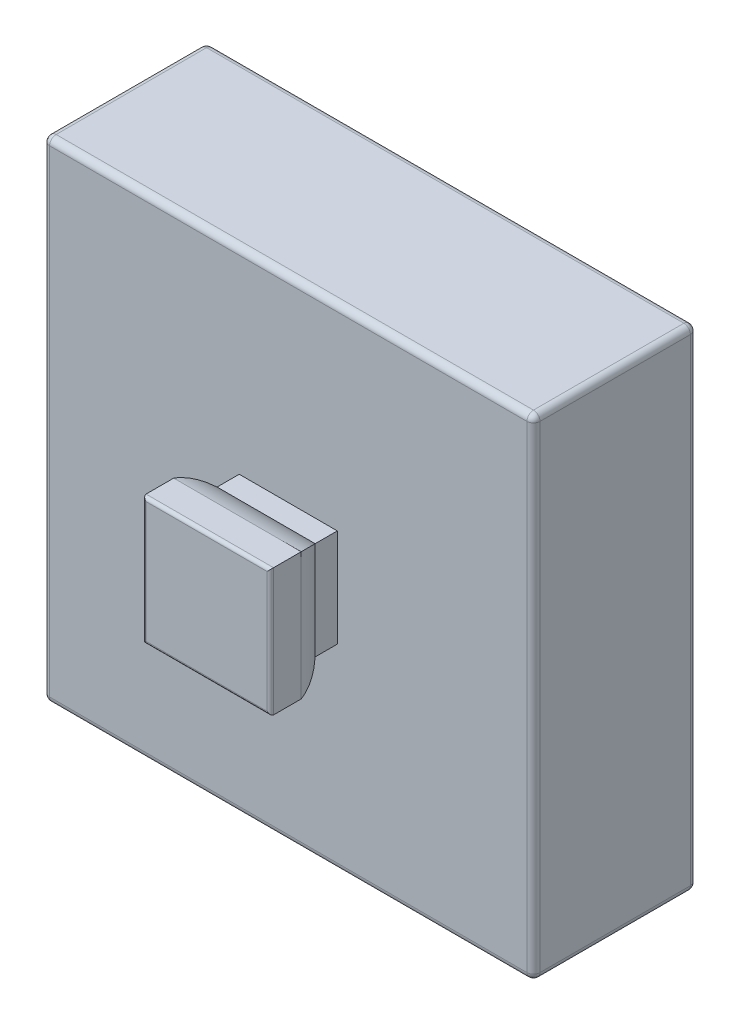
SolidWorks part; units mm, degrees
ref_plane "前视基准面" through (0, 0, 0) normal (0, 0, 1) x (1, 0, 0)
ref_plane "上视基准面" through (0, 0, 0) normal (0, 1, 0) x (1, 0, 0)
ref_plane "右视基准面" through (0, 0, 0) normal (1, 0, 0) x (0, 0, -1)
sketch "草图1" plane through (0, 0, 0) normal (0, 0, 1) x (1, 0, 0)
  line L1 (-7.5, -7.5) -> (7.5, -7.5)
  line L2 (-7.5, -7.5) -> (-7.5, 7.5)
  line L3 (-7.5, 7.5) -> (7.5, 7.5)
  line L4 (7.5, -7.5) -> (7.5, 7.5)
extrude "凸台-拉伸1" add sketch "草图1" against normal blind 5
sketch "草图2" plane through (0, 0, 0) normal (0, 0, 1) x (1, 0, 0)
  line L1 (-1.5, -1.5) -> (1.5, -1.5)
  line L2 (-1.5, -1.5) -> (-1.5, 1.5)
  line L3 (-1.5, 1.5) -> (1.5, 1.5)
  line L4 (1.5, -1.5) -> (1.5, 1.5)
extrude "凸台-拉伸2" add sketch "草图2" along normal blind 1
sketch "草图3" plane through (0, 0, 0) normal (0, 1, 0) x (1, 0, 0)
  line L0 (-1.95, -2.5) -> (1.95, -2.5)
  line L1 (-1.95, -2.5) -> (-1.95, -1.5556)
  line L2 (-1.5, -1) -> (-1.5, 0) construction
  line L3 (-1.5, -0.6771) -> (1.5, -0.6771)
  line L4 (1.95, -2.5) -> (1.95, -1.5556)
  arc A0 (1.95, -1.5556) -> (1.5, -0.6771) centre (0, -2) ccw
  arc A1 (-1.5, -0.6771) -> (-1.95, -1.5556) centre (0, -2) ccw
extrude "凸台-拉伸3" add sketch "草图3" along normal blind 2 and the other way blind 2
sketch "草图4" plane through (0, 0, 0) normal (1, 0, 0) x (0, 0, -1)
  line L0 (-2.5, 1.95) -> (-1.5556, 1.95)
  line L1 (-2.5, 1.95) -> (-2.5, 2)
  line L2 (-2.5, -2) -> (-2.5, 2) construction
  line L3 (-2.5, 2) -> (-0.6771, 2)
  line L4 (-0.6771, 2) -> (-0.6771, 1.5)
  line L5 (-2.5, -2) -> (-0.6771, -2)
  line L6 (-0.6771, -2) -> (-0.6771, -1.5)
  line L7 (-2.5, -1.95) -> (-1.5556, -1.95)
  line L8 (-2.5, -1.95) -> (-2.5, -2)
  arc A0 (-0.6771, 1.5) -> (-1.5556, 1.95) centre (-2, 0) ccw
  arc A2 (-1.5556, -1.95) -> (-0.6771, -1.5) centre (-2, 0) ccw
extrude "切除-拉伸1" cut sketch "草图4" against normal up to next and the other way up to next
fillet "圆角1" radius 0.1 4 edges at (0, -1.95, 2.5) (-1.95, 0, 2.5) (0, 1.95, 2.5) (1.95, 0, 2.5)
ref_plane "基准面1" through (0, 0, -2.5) normal (0, 0, 1) x (1, 0, 0)
mirror "镜向1" about plane through (0, 0, -2.5) normal (0, 0, 1) of "凸台-拉伸2", "凸台-拉伸3", "切除-拉伸1", "圆角1"
fillet "圆角2" radius 0.2 12 edges at (0, -7.5, -5) (0, -7.5, 0) (-7.5, -7.5, -2.5) (-7.5, 0, -5) (-7.5, 0, 0) (-7.5, 7.5, -2.5) (0, 7.5, -5) (0, 7.5, 0) (7.5, 7.5, -2.5) (7.5, 0, -5) (7.5, -7.5, -2.5) (7.5, 0, 0)
